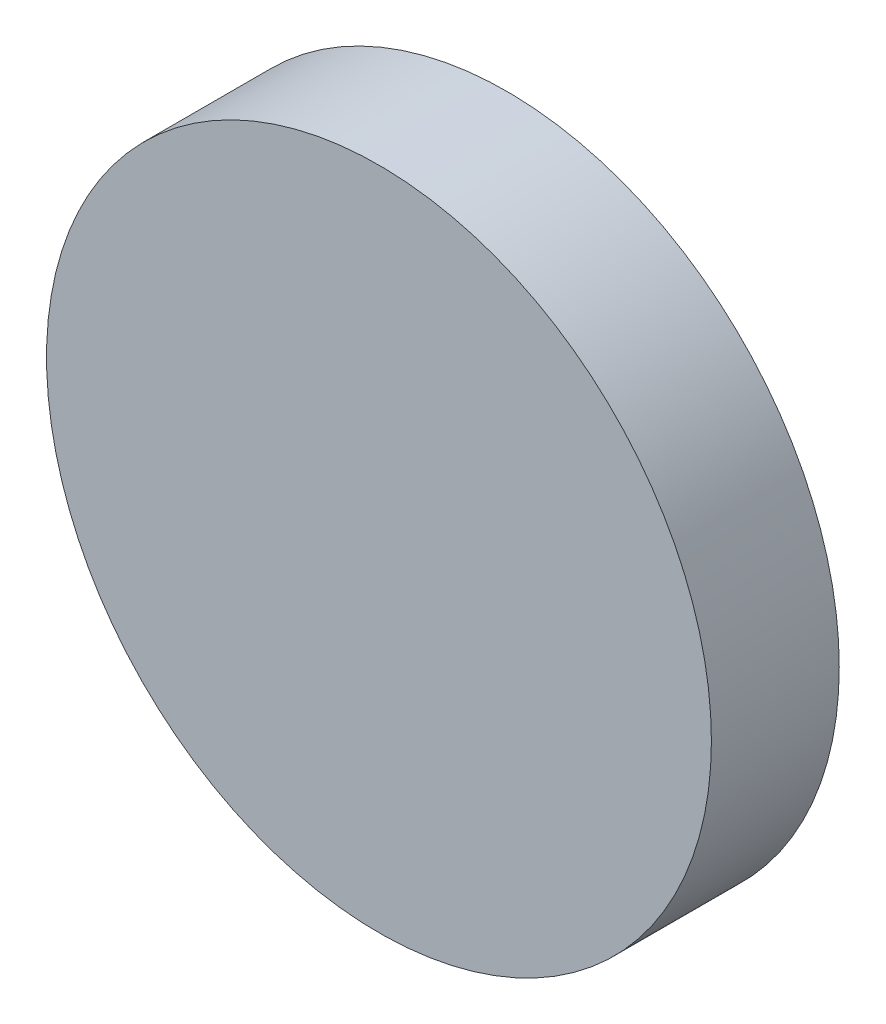
SolidWorks part; units mm, degrees
ref_plane "前视基准面" through (0, 0, 0) normal (0, 0, 1) x (1, 0, 0)
ref_plane "上视基准面" through (0, 0, 0) normal (0, 1, 0) x (1, 0, 0)
ref_plane "右视基准面" through (0, 0, 0) normal (1, 0, 0) x (0, 0, -1)
sketch "草图1" plane through (0, 0, 0) normal (0, 0, 1) x (1, 0, 0)
  circle A0 centre (0, 0) radius 130
extrude "凸台-拉伸1" add sketch "草图1" along normal blind 50
sketch "草图4" plane through (0, 0, 0) normal (0, 0, -1) x (-1, 0, 0)
  circle A2 centre (-56.5685, 56.5685) radius 10
  circle A3 centre (56.5685, 56.5685) radius 10
  circle A4 centre (-56.5685, -56.5685) radius 10
  circle A5 centre (56.5685, -56.5685) radius 10
  point P0 (0, 0)
extrude "凸台-拉伸4" add sketch "草图4" along normal blind 10
